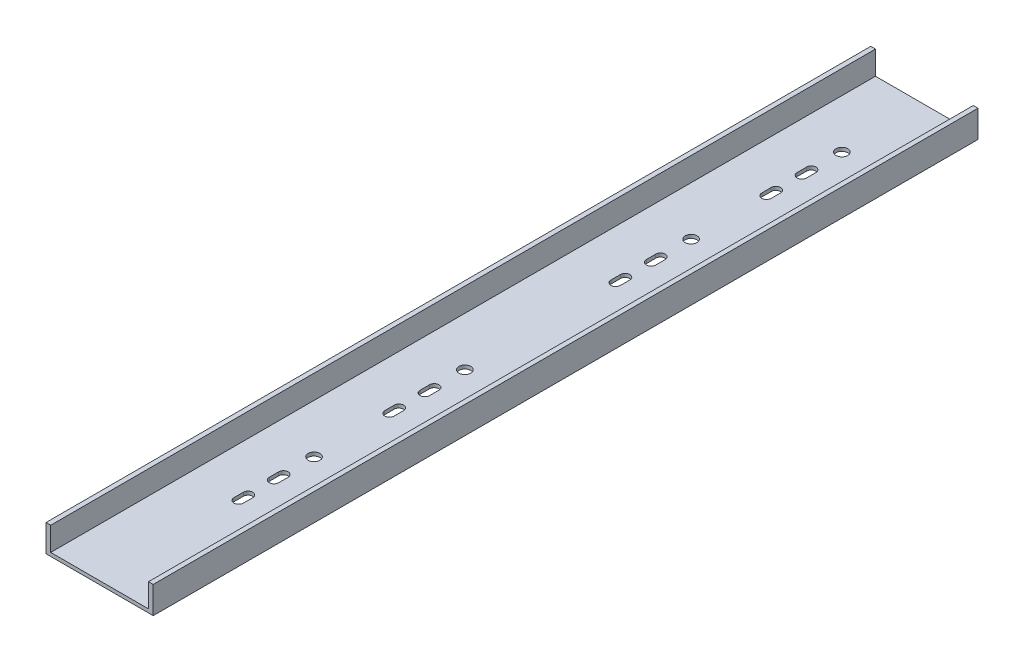
SolidWorks part; units mm, degrees
material "6061 合金"
ref_plane "前视基准面" through (0, 0, 0) normal (0, 0, 1) x (1, 0, 0)
ref_plane "上视基准面" through (0, 0, 0) normal (0, 1, 0) x (1, 0, 0)
ref_plane "右视基准面" through (0, 0, 0) normal (1, 0, 0) x (0, 0, -1)
sketch "草图1" plane through (0, 0, 0) normal (0, 0, 1) x (1, 0, 0)
  line L0 (-22.75, 0) -> (22.75, 0)
  line L1 (22.75, 0) -> (22.75, 11.5)
  line L2 (22.75, 11.5) -> (20.75, 11.5)
  line L3 (20.75, 11.5) -> (20.75, 1.5)
  line L4 (20.75, 1.5) -> (-20.75, 1.5)
  line L5 (0, 1.5) -> (0, -5.0447) construction
  line L6 (-20.75, 11.5) -> (-20.75, 1.5)
  line L7 (-22.75, 11.5) -> (-20.75, 11.5)
  line L8 (-22.75, 0) -> (-22.75, 11.5)
  point P12 (0, 0)
  dimension "D1" = 45.5
  dimension "D2" = 11.5
  dimension "D3" = 10
  dimension "D4" = 2
extrude "凸台-拉伸1" add sketch "草图1" along normal blind 350
sketch "草图2" plane through (0, 0, 0) normal (0, -1, 0) x (1, 0, 0)
  line L0 (-22.75, 0) -> (22.75, 0) construction
  line L1 (2, 52) -> (2, 48)
  line L2 (-2, 52) -> (-2, 48)
  line L3 (-2, 67) -> (-2, 63)
  line L4 (2, 67) -> (2, 63)
  circle A0 centre (0, 35) radius 2.5
  arc A1 (2, 52) -> (-2, 52) centre (0, 52) ccw
  arc A2 (-2, 48) -> (2, 48) centre (0, 48) ccw
  arc A3 (-2, 63) -> (2, 63) centre (0, 63) ccw
  arc A4 (2, 67) -> (-2, 67) centre (0, 67) ccw
  dimension "D2" = 5
  dimension "D3" = 11
  dimension "D4" = 4
  dimension "D1" = 35
  dimension "D5" = 4
  dimension "D6" = 13
  dimension "D7" = 2
extrude "切除-拉伸1" cut sketch "草图2" against normal blind 350
pattern_linear "阵列(线性)1" count 2 spacing 64 along (0, 0, 1) of "切除-拉伸1"
pattern_linear "阵列(线性)2" count 2 spacing 160 along (0, 0, 1) of "切除-拉伸1"
pattern_linear "阵列(线性)3" count 2 spacing 160 along (0, 0, 1) of "阵列(线性)1"
